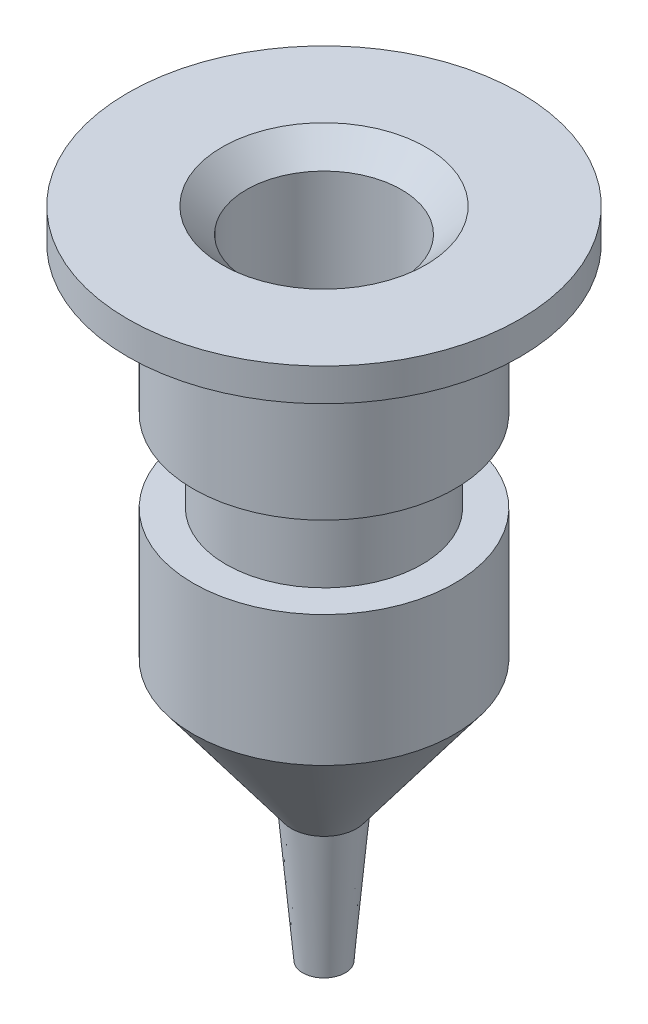
SolidWorks part; units mm, degrees
ref_plane "Front Plane" through (0, 0, 0) normal (0, 0, 1) x (1, 0, 0)
ref_plane "Top Plane" through (0, 0, 0) normal (0, 1, 0) x (1, 0, 0)
ref_plane "Right Plane" through (0, 0, 0) normal (1, 0, 0) x (0, 0, -1)
ref_plane "Plane1" through (0, 0, 0) normal (0, 0, -1) x (-1, 0, 0)
sketch "Sketch1" plane through (0, 0, 0) normal (0, 0, -1) x (-1, 0, 0)
  line L0 (-4, 12) -> (-4, 8)
  line L1 (-4, 8) -> (-1, 4)
  line L2 (-1, 4) -> (-0.65, 0)
  line L3 (-0.65, 0) -> (-0.4, 0)
  line L4 (-0.4, 0) -> (-0.4, 5)
  line L5 (-0.4, 5) -> (-1, 5.3464)
  line L6 (-1, 5.3464) -> (-1, 10)
  line L7 (-1, 10) -> (-2.37, 10.791)
  line L8 (-2.37, 10.791) -> (-2.37, 19.25)
  line L9 (-2.37, 19.25) -> (-3.12, 20)
  line L10 (-3.12, 20) -> (-6, 20)
  line L11 (-6, 20) -> (-6, 19)
  line L12 (-6, 19) -> (-4, 19)
  line L13 (-4, 19) -> (-4, 14.5)
  line L14 (-4, 14.5) -> (-3, 14.5)
  line L15 (-3, 14.5) -> (-3, 12)
  line L16 (-3, 12) -> (-4, 12)
  line L17 (0, 0) -> (0, 20) construction
revolve "Revolve1" add sketch "Sketch1" angle 360 about L17
